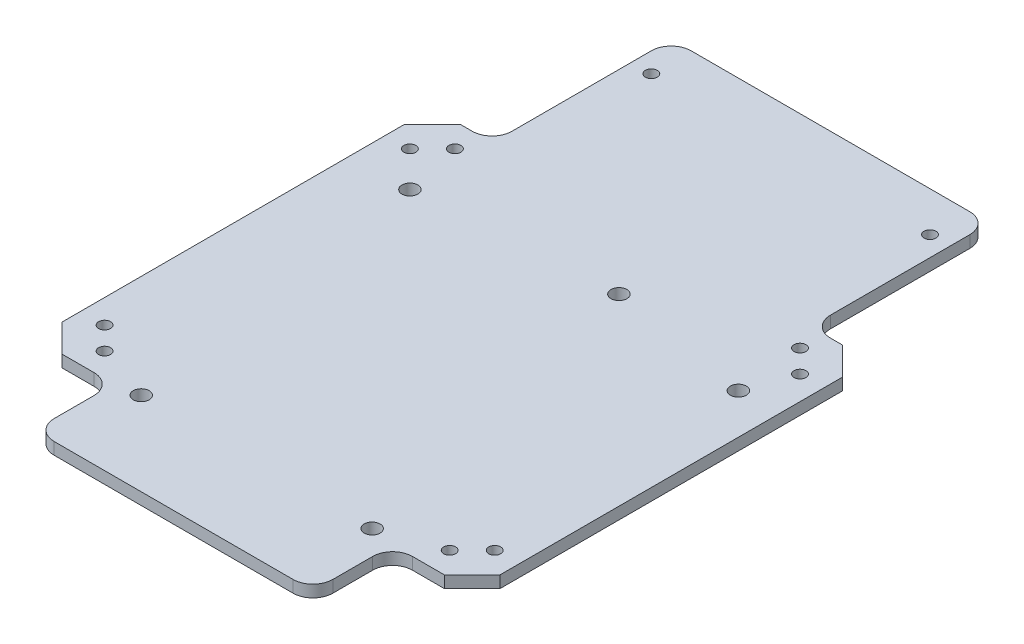
SolidWorks part; units mm, degrees
material "Thornel Mat VMA"
ref_plane "前视基准面" through (0, 0, 0) normal (0, 0, 1) x (1, 0, 0)
ref_plane "上视基准面" through (0, 0, 0) normal (0, 1, 0) x (1, 0, 0)
ref_plane "右视基准面" through (0, 0, 0) normal (1, 0, 0) x (0, 0, -1)
other "Configuration Table"
sketch "草图1" plane through (0, 0, 0) normal (0, 1, 0) x (1, 0, 0)
  line L0 (0, 0) -> (63.1315, 0) construction
  line L1 (-55, -50) -> (55, -50)
  line L2 (-55, -50) -> (-55, 50)
  line L3 (-55, 50) -> (55, 50)
  line L4 (55, -50) -> (55, 50)
  line L5 (-55, -50) -> (55, 50) construction
  line L6 (-55, 50) -> (55, -50) construction
  line L7 (0, 0) -> (0, 58.586) construction
  line L8 (43.3431, 44) -> (49, 38.3431) construction
  line L9 (40, 50) -> (40, 95)
  line L10 (40, 95) -> (-40, 95)
  line L11 (-40, 50) -> (-40, 95)
  circle A4 centre (43.3431, 44) radius 1.5
  circle A5 centre (49, 38.3431) radius 1.5
  circle A6 centre (49, -38.3431) radius 1.5
  circle A7 centre (43.3431, -44) radius 1.5
  circle A8 centre (-43.3431, -44) radius 1.5
  circle A9 centre (-49, -38.3431) radius 1.5
  circle A10 centre (-49, 38.3431) radius 1.5
  circle A11 centre (-43.3431, 44) radius 1.5
  circle A12 centre (-35, 85) radius 1.5
  circle A13 centre (35, 85) radius 1.5
  point P0 (0, 0)
  point P14 (0, 95)
  dimension "D3" = 45
  dimension "D5" = 3
  dimension "D6" = 3
  dimension "D7" = 3
  dimension "D8" = 8
  dimension "D13" = 70
  dimension "D1" = 110
  dimension "D2" = 100
  dimension "D4" = 80
  dimension "D9" = 45
  dimension "D10" = 6
  dimension "D11" = 6
  dimension "D12" = 85
extrude "凸台-拉伸1" add sketch "草图1" along normal blind 3 contours L1 L4 L3 L2 A10 A9 A8 A6 A5 A4 A7 A11 | L11 L3 L9 L10
chamfer "倒角1" distance 7 angle 45 4 edges at (-55, 1.5, 50) (-55, 1.5, -50) (55, 1.5, 50) (55, 1.5, -50)
fillet "圆角1" radius 5 4 edges at (40, 1.5, -50) (40, 1.5, -95) (-40, 1.5, -95) (-40, 1.5, -50)
sketch "草图2" plane through (0, 3, 0) normal (0, 1, 0) x (1, 0, 0)
  line L0 (0, 0) -> (70.5202, 0) construction
  line L1 (0, 0) -> (0, -85.6889) construction
  line L2 (-35, -50) -> (35, -50)
  line L3 (-48, -50) -> (48, -50) construction
  line L4 (35, -50) -> (35, -70)
  line L5 (35, -70) -> (-35, -70)
  line L6 (-35, -50) -> (-35, -70)
  point P11 (0, -50)
  point P12 (0, -70)
  dimension "D1" = 20
  dimension "D2" = 70
extrude "凸台-拉伸2" add sketch "草图2" against normal blind 3
sketch "草图3" plane through (0, 3, 0) normal (0, 1, 0) x (1, 0, 0)
  line L0 (0, 0) -> (95.6793, 0) construction
  line L1 (0, 0) -> (0, 105.8926) construction
  line L2 (0, 42) -> (35, 42) construction
  line L3 (35, 42) -> (49.14, 27.86) construction
  line L4 (49.14, 27.86) -> (49.14, -27.14) construction
  line L5 (49.14, -27.14) -> (32.86, -41.28) construction
  line L6 (32.86, -41.28) -> (32.86, -66) construction
  line L7 (32.86, -66) -> (-33.14, -66) construction
  line L8 (-33.14, -66) -> (-33.14, -42.14) construction
  line L9 (-33.14, -42.14) -> (-49.14, -27.14) construction
  line L10 (-49.14, -27.14) -> (-49.14, 27.86) construction
  line L11 (-49.14, 27.86) -> (-35, 42) construction
  line L12 (-35, 42) -> (0, 42) construction
  circle A0 centre (-40.14, 29.5) radius 2
  circle A1 centre (44.86, 27) radius 2
  circle A2 centre (-29.14, -49) radius 2
  circle A3 centre (28.86, -49) radius 2
  circle A4 centre (8.86, 33) radius 2
  dimension "D14" = 4
  dimension "D15" = 4
  dimension "D16" = 4
  dimension "D17" = 4
  dimension "D20" = 15
  dimension "D22" = 91
  dimension "D26" = 4
  dimension "D1" = 70
  dimension "D2" = 14.14
  dimension "D3" = 14.14
  dimension "D4" = 55
  dimension "D5" = 16.28
  dimension "D6" = 14.14
  dimension "D7" = 108
  dimension "D8" = 66
  dimension "D9" = 16
  dimension "D10" = 55
  dimension "D11" = 84.14
  dimension "D12" = 42
  dimension "D13" = 35
  dimension "D18" = 12.5
  dimension "D19" = 9
  dimension "D21" = 94
  dimension "D23" = 78
  dimension "D24" = 20
  dimension "D25" = 91
  dimension "D27" = 9
  dimension "D28" = 58
extrude "切除-拉伸1" cut sketch "草图3" against normal blind 3
fillet "圆角2" radius 5 4 edges at (35, 1.5, 50) (35, 1.5, 70) (-35, 1.5, 70) (-35, 1.5, 50)
